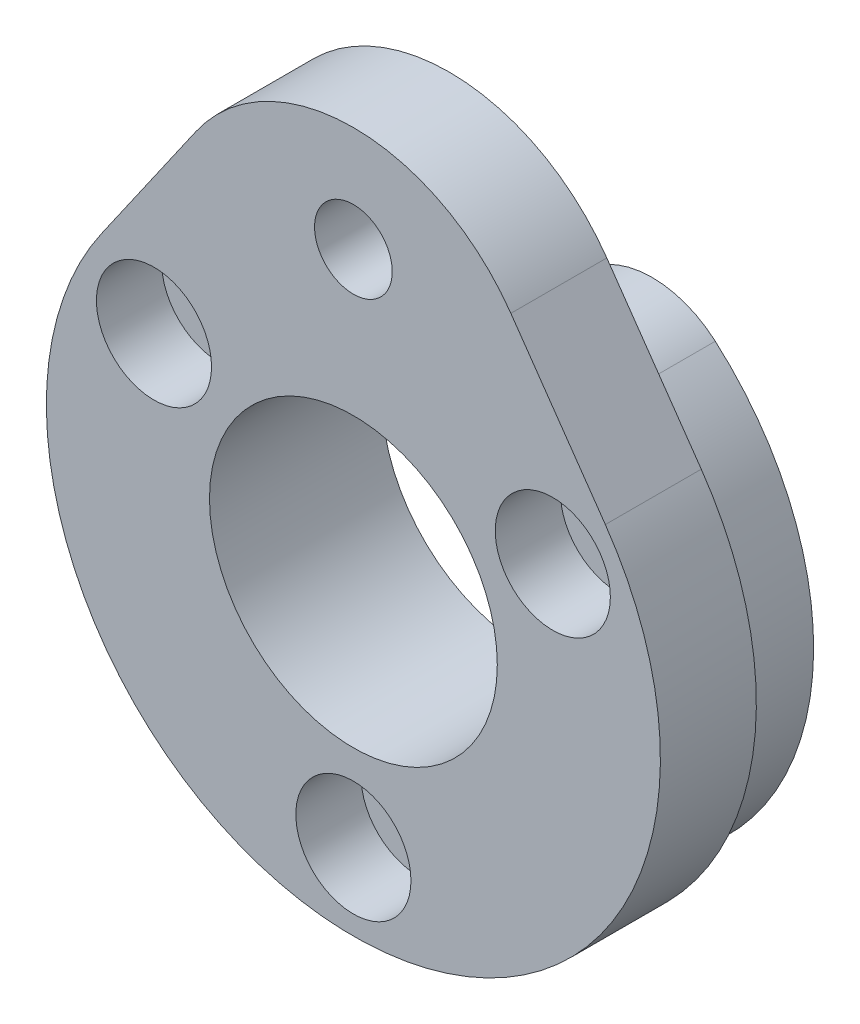
SolidWorks part; units mm, degrees
material "ABS"
ref_plane "前视基准面" through (0, 0, 0) normal (0, 0, 1) x (1, 0, 0)
ref_plane "上视基准面" through (0, 0, 0) normal (0, 1, 0) x (1, 0, 0)
ref_plane "右视基准面" through (0, 0, 0) normal (1, 0, 0) x (0, 0, -1)
other "Configuration Table"
sketch "草图1" plane through (0, 0, 0) normal (0, 0, 1) x (1, 0, 0)
  line L0 (0, 0) -> (0, 15) construction
  line L1 (0, 15) -> (0, 28) construction
  line L2 (0, 28) -> (13.1304, 9.1429)
  line L3 (0, 28) -> (-13.1304, 9.1429)
  line L4 (0, 0) -> (0, -16) construction
  line L5 (10.3923, -6) -> (0, 0) construction
  circle A0 centre (0, 0) radius 16 construction
  circle A1 centre (0, 15) radius 2.025
  arc A2 (-13.1304, 9.1429) -> (13.1304, 9.1429) centre (0, 0) ccw
  circle A3 centre (0, 0) radius 12 construction
  circle A9 centre (0, 0) radius 7.5
  dimension "D1" = 32
  dimension "D3" = 4.05
  dimension "D5" = 24
  dimension "D9" = 15
  dimension "D2" = 15
  dimension "D4" = 13
  dimension "D7" = 60
extrude "凸台-拉伸1" add sketch "草图1" along normal blind 5
fillet "圆角1" radius 10 1 edges at (0, 28, 2.5)
sketch "草图6" plane through (0, 0, 0) normal (0, 0, -1) x (-1, 0, 0)
  line L0 (0, 0) -> (-10.3923, -6) construction
  line L2 (0, 0) -> (10.3923, -6) construction
  line L3 (0, 0) -> (0, -16) construction
  circle A4 centre (0, 0) radius 7.5
  arc A5 (-13.1304, 9.1429) -> (13.1304, 9.1429) centre (0, 0) ccw construction
  circle A6 centre (0, 0) radius 14.985
  dimension "D3" = 15
  dimension "D4" = 29.97
  dimension "D5" = 60
  dimension "D6" = 60
  dimension "D7" = 12
  dimension "D8" = 12
extrude "凸台-拉伸2" add sketch "草图6" along normal blind 4
sketch "草图2" plane through (0, 0, 5) normal (0, 0, 1) x (1, 0, 0)
  line L0 (0, 0) -> (0, -16) construction
  arc A0 (-13.1304, 9.1429) -> (13.1304, 9.1429) centre (0, 0) ccw construction
  point P6 (0, -12)
  point P7 (-10.3923, 6)
  point P10 (10.3923, 6)
  dimension "D1" = 12
  dimension "D2" = 3
hole_wizard "M3 六角圆柱头螺钉的柱形沉头孔2" positions "草图2" profile "草图3" counterbore size "M3" standard "GB" end condition up to next
sketch "草图3" plane through (10.3923, 6, 5) normal (1, 0, 0) x (0, -1, 0)
  line L0 (0, 0) -> (0, 9)
  line L1 (0, 9) -> (1.6, 9)
  line L3 (1.6, 9) -> (1.6, 3.4)
  line L4 (1.6, 3.4) -> (3, 3.4)
  line L5 (3, 3.4) -> (3, 0)
  line L7 (3, 0) -> (0, 0)
  line L11 (0, -6.35) -> (0, 107.95) construction
  dimension "通孔孔直径" = 3.2
  dimension "通孔孔深度" = 9
  dimension "柱形沉头孔直径" = 6
  dimension "柱形沉头孔深度" = 3.4
sketch "草图8" plane through (0, 0, -4) normal (0, 0, -1) x (-1, 0, 0)
  circle A0 centre (0.0809, 14.9848) radius 5
  circle A1 centre (0, 0) radius 14.985 construction
  dimension "D1" = 10
extrude "切除-拉伸1" cut sketch "草图8" against normal up to surface (4 mm away) up to face at (0, 1.02, 0)
sketch "草图4" plane through (0, 0, 0) normal (0, 0, -1) x (-1, 0, 0)
  circle A2 centre (0, 15) radius 3.75
  dimension "D1" = 7.5
chamfer "倒角1" [suppressed] distance 0.2 angle 45
extrude "切除-拉伸2" cut sketch "草图4" against normal blind 2.05
fillet "圆角2" radius 5 2 edges at (-5.0063, 14.124, -2) (4.8534, 14.1773, -2)
chamfer "倒角3" [suppressed] distance 0.5 angle 45
sketch "草图9" plane through (0, 0, -4) normal (0, 0, -1) x (-1, 0, 0)
  line L0 (0, 0) -> (10.3923, -6) construction
  line L1 (0, 0) -> (0, -12) construction
  line L2 (0, 0) -> (-10.3923, -6) construction
  circle A0 centre (0, 0) radius 12 construction
  point P7 (10.3923, -6)
  point P8 (-10.3923, -6)
  dimension "D1" = 24
  dimension "D2" = 60
  dimension "D3" = 60
hole_wizard "Ø3.0mm 暗销孔1" positions "草图9" profile "草图10" hole size "Ø3.0" standard "GB"
sketch "草图10" plane through (10.3923, -6, -4) normal (1, 0, 0) x (0, 1, 0)
  line L0 (0, 0) -> (0, 4.9013)
  line L1 (0, 4.9013) -> (1.5, 4)
  line L2 (1.5, 4) -> (1.5, 0)
  line L5 (1.5, 0) -> (0, 0)
  line L10 (0, 4.9013) -> (-1.5, 4) construction
  line L11 (0, -6.35) -> (0, 107.95) construction
  dimension "孔直径" = 3
  dimension "孔深度" = 4
  dimension "导头角度" = 118
sketch "草图11" plane through (0, 0, 5) normal (0, 0, 1) x (1, 0, 0)
  circle A0 centre (0, 15) radius 3.6
  dimension "D1" = 7.2
extrude "切除-拉伸3" [suppressed] cut sketch "草图11" against normal blind 2
chamfer "倒角4" [suppressed] distance 0.2 angle 45
chamfer "倒角5" [suppressed] distance 0.2 angle 45
